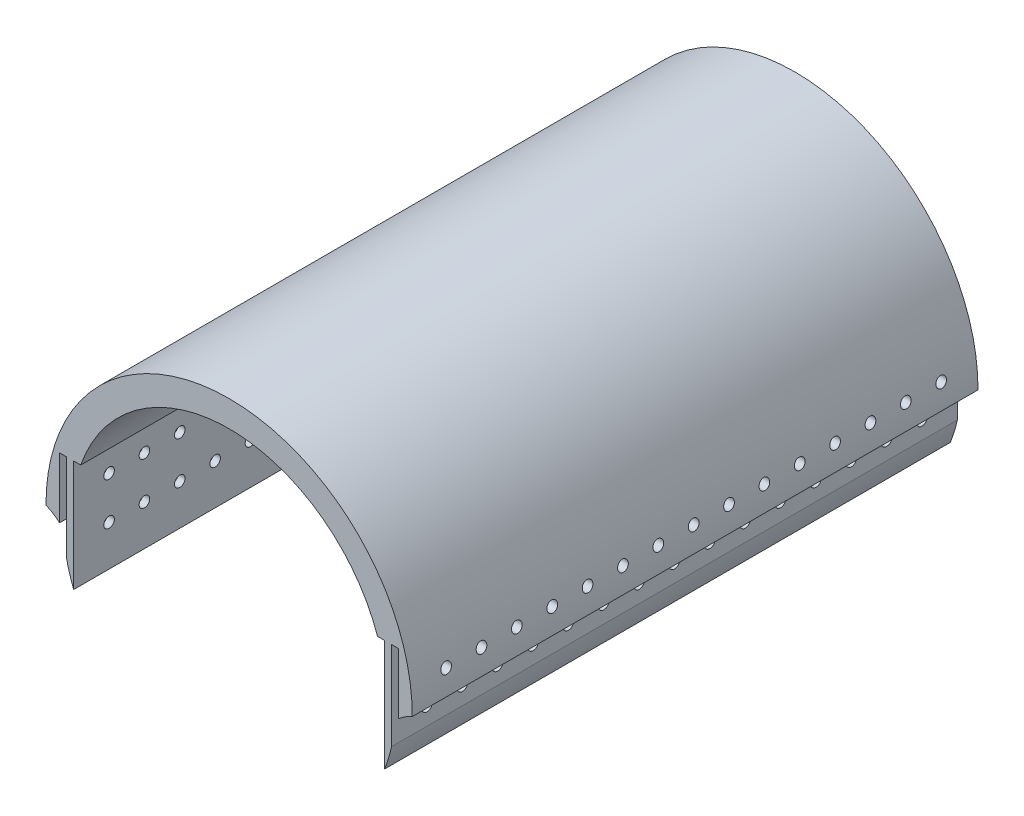
SolidWorks part; units mm, degrees
ref_plane "Front Plane" through (0, 0, 0) normal (0, 0, 1) x (1, 0, 0)
ref_plane "Top Plane" through (0, 0, 0) normal (0, 1, 0) x (1, 0, 0)
ref_plane "Right Plane" through (0, 0, 0) normal (1, 0, 0) x (0, 0, -1)
sketch "Sketch1" plane through (0, 0, 0) normal (0, 0, 1) x (1, 0, 0)
  line L0 (43.962, 14.4195) -> (41.962, 14.4195) construction
  line L1 (43.962, -17.082) -> (43.962, 14.4195) construction
  line L2 (45.962, 14.4195) -> (45.962, -10.5805) construction
  line L3 (47.962, 14.4195) -> (45.962, 14.4195) construction
  line L4 (-43.962, 14.4195) -> (-43.962, -17.082) construction
  line L5 (-41.962, 14.4195) -> (-43.962, 14.4195) construction
  line L6 (-45.962, -10.5805) -> (-45.962, 14.4195) construction
  line L7 (-45.962, 14.4195) -> (-47.962, 14.4195) construction
  line L8 (47.962, -6.2527) -> (47.962, 14.4195) construction
  line L9 (-47.962, 14.4195) -> (-47.962, -6.2527) construction
  line L10 (43.962, 14.4195) -> (41.962, 14.4195)
  line L11 (43.962, -17.082) -> (43.962, 14.4195)
  line L12 (45.962, 14.4195) -> (45.962, -10.5805)
  line L13 (47.962, 14.4195) -> (45.962, 14.4195)
  line L14 (-43.962, 14.4195) -> (-43.962, -17.082)
  line L15 (-41.962, 14.4195) -> (-43.962, 14.4195)
  line L16 (-45.962, -10.5805) -> (-45.962, 14.4195)
  line L17 (-45.962, 14.4195) -> (-47.962, 14.4195)
  line L18 (47.962, -6.2527) -> (47.962, 14.4195)
  line L19 (-47.962, 14.4195) -> (-47.962, -6.2527)
  arc A0 (43.962, -17.082) -> (45.962, -10.5805) centre (0, 0) ccw construction
  arc A1 (-45.962, -10.5805) -> (-43.962, -17.082) centre (0, 0) ccw construction
  arc A2 (51.7903, -0.3127) -> (47.962, -2.7456) centre (57.2847, -13.187) ccw construction
  arc A3 (-47.962, -2.7456) -> (-51.7903, -0.3127) centre (-57.2847, -13.187) ccw construction
  arc A4 (43.962, -17.082) -> (45.962, -10.5805) centre (0, 0) ccw
  arc A5 (-45.962, -10.5805) -> (-43.962, -17.082) centre (0, 0) ccw
  arc A6 (51.7903, -0.3127) -> (47.962, -2.7456) centre (57.2847, -13.187) ccw
  arc A7 (-47.962, -2.7456) -> (-51.7903, -0.3127) centre (-57.2847, -13.187) ccw
  arc A8 (-51.7903, -0.3127) -> (51.7903, -0.3127) centre (0, -0.1015) cw
  arc A9 (-41.962, 14.4195) -> (41.962, 14.4195) centre (0, -0.1015) cw
extrude "Boss-Extrude1" add sketch "Sketch1" along normal blind 160 contours L15 A9 L10 L11 A4 L12 L13 L18 A6 A8 A7 L19 L17 L16 A5 L14
sketch "Sketch2" plane through (43.962, 0, 0) normal (-1, 0, 0) x (0, 0, 1)
  line L0 (10, 14.4195) -> (10, -17.082) construction
  line L1 (160, 14.4195) -> (0, 14.4195) construction
  line L2 (160, -17.082) -> (0, -17.082) construction
  line L3 (0, -17.082) -> (0, 14.4195) construction
  line L4 (160, 14.4195) -> (0, 14.4195) construction
  circle A0 centre (10, 6.4195) radius 1.5
  circle A1 centre (10, -5.5805) radius 1.5
  circle A2 centre (20, 6.4195) radius 1.5
  circle A3 centre (20, -5.5805) radius 1.5
  circle A4 centre (30, 6.4195) radius 1.5
  circle A5 centre (30, -5.5805) radius 1.5
  circle A6 centre (40, 6.4195) radius 1.5
  circle A7 centre (40, -5.5805) radius 1.5
  circle A8 centre (50, 6.4195) radius 1.5
  circle A9 centre (50, -5.5805) radius 1.5
  circle A10 centre (60, 6.4195) radius 1.5
  circle A11 centre (60, -5.5805) radius 1.5
  circle A12 centre (70, 6.4195) radius 1.5
  circle A13 centre (70, -5.5805) radius 1.5
  circle A14 centre (80, 6.4195) radius 1.5
  circle A15 centre (80, -5.5805) radius 1.5
  circle A16 centre (90, 6.4195) radius 1.5
  circle A17 centre (90, -5.5805) radius 1.5
  circle A18 centre (100, 6.4195) radius 1.5
  circle A19 centre (100, -5.5805) radius 1.5
  circle A20 centre (110, 6.4195) radius 1.5
  circle A21 centre (110, -5.5805) radius 1.5
  circle A22 centre (120, 6.4195) radius 1.5
  circle A23 centre (120, -5.5805) radius 1.5
  circle A24 centre (130, 6.4195) radius 1.5
  circle A25 centre (130, -5.5805) radius 1.5
  circle A26 centre (140, 6.4195) radius 1.5
  circle A27 centre (140, -5.5805) radius 1.5
  circle A28 centre (150, 6.4195) radius 1.5
  circle A29 centre (150, -5.5805) radius 1.5
  dimension "D2" = 3
  dimension "D4" = 3
  dimension "D5" = 12
  dimension "D1" = 10
  dimension "D3" = 8
  dimension "D6" = 15
extrude "Cut-Extrude1" cut sketch "Sketch2" against normal through all both and the other way through all
